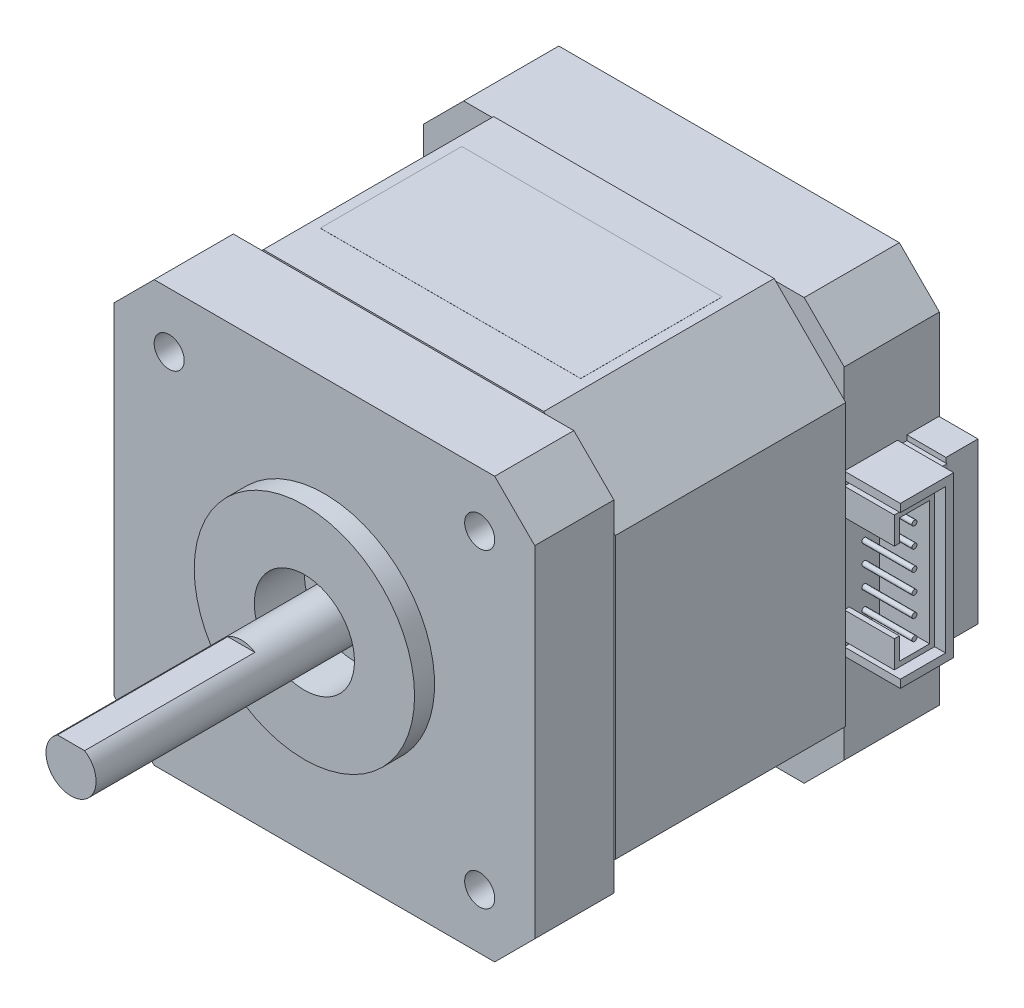
SolidWorks part; units mm, degrees
ref_plane "Front Plane" through (0, 0, 0) normal (0, 0, 1) x (1, 0, 0)
ref_plane "Top Plane" through (0, 0, 0) normal (0, 1, 0) x (1, 0, 0)
ref_plane "Right Plane" through (0, 0, 0) normal (1, 0, 0) x (0, 0, -1)
sketch "Sketch1" plane through (0, 0, 0) normal (0, 0, 1) x (1, 0, 0)
  line L0 (-17, 21) -> (-21, 17)
  line L1 (-17, -21) -> (17, -21)
  line L2 (-21, -17) -> (-21, 17)
  line L3 (-17, 21) -> (17, 21)
  line L4 (21, -17) -> (21, 17)
  line L5 (21, 17) -> (17, 21)
  line L6 (17, -21) -> (21, -17)
  line L12 (-21, -17) -> (-17, -21)
  point P0 (0, 0)
  point P15 (0, 0)
  dimension "D1" = 4
extrude "Boss-Extrude1" add sketch "Sketch1" along normal blind 9.5
sketch "Sketch2" plane through (0, 0, 9.5) normal (0, 0, 1) x (1, 0, 0)
  line L0 (14, 21.15) -> (21.15, 14)
  line L5 (-14, -21.15) -> (14, -21.15)
  line L6 (-21.15, -14) -> (-21.15, 14)
  line L7 (-14, 21.15) -> (14, 21.15)
  line L12 (21.15, -14) -> (21.15, 14)
  line L14 (17.5, -17.5) -> (17.575, -17.575) construction
  line L15 (-21.15, 14) -> (-14, 21.15)
  line L16 (21.15, -14) -> (14, -21.15)
  line L17 (-14, -21.15) -> (-21.15, -14)
  line L18 (17.5, 17.5) -> (17.575, 17.575) construction
  point P0 (0, 0)
  point P1 (0, 0)
  point P13 (0, 0)
  point P16 (0, 0)
  point P19 (0, 0)
  point P22 (0, 0)
  point P29 (0, 0)
  dimension "D1" = 4
  dimension "D5" = 4
extrude "Boss-Extrude2" add sketch "Sketch2" along normal blind 23
sketch "Sketch3" plane through (0, 0, 32.5) normal (0, 0, 1) x (1, 0, 0)
  line L0 (-17, 21) -> (17, 21)
  line L1 (17, 21) -> (21, 17)
  line L2 (21, 17) -> (21, -17)
  line L3 (21, -17) -> (17, -21)
  line L4 (17, -21) -> (-17, -21)
  line L5 (-17, -21) -> (-21, -17)
  line L6 (-21, -17) -> (-21, 17)
  line L7 (-21, 17) -> (-17, 21)
extrude "Boss-Extrude3" add sketch "Sketch3" along normal blind 7.9
sketch "Sketch5" plane through (0, 0, 40.4) normal (0, 0, 1) x (1, 0, 0)
  circle A0 centre (0, 0) radius 11
  circle A1 centre (0, 0) radius 5
  dimension "D1" = 22
  dimension "D2" = 10
extrude "Boss-Extrude4" add sketch "Sketch5" along normal blind 2
sketch "Sketch6" plane through (0, 0, 40.4) normal (0, 0, 1) x (1, 0, 0)
  circle A0 centre (0, 0) radius 5
extrude "Cut-Extrude1" cut sketch "Sketch6" against normal blind 3
sketch "Sketch7" plane through (0, 0, 37.4) normal (0, 0, 1) x (1, 0, 0)
  circle A0 centre (0, 0) radius 2.5
  dimension "D1" = 5
extrude "Boss-Extrude5" add sketch "Sketch7" along normal up to surface (5 mm away) up to face at (11, 0, 42.4)
sketch "Sketch8" plane through (0, 0, 42.4) normal (0, 0, 1) x (1, 0, 0)
  circle A0 centre (0, 0) radius 2.5
extrude "Boss-Extrude6" add sketch "Sketch8" along normal blind 23.3
sketch "Sketch9" plane through (0, 0, 65.7) normal (0, 0, 1) x (1, 0, 0)
  line L0 (-2.3166, 2.1) -> (3.6979, 2.1)
  line L1 (3.6979, 2.1) -> (-0.1236, 3.991)
  line L2 (-0.1236, 3.991) -> (-2.3166, 2.1)
extrude "Cut-Extrude2" cut sketch "Sketch9" against normal blind 17
sketch "Sketch10" plane through (0, 21.15, 0) normal (0, 1, 0) x (1, 0, 0)
  line L1 (-13, -13.6909) -> (13, -13.6909)
  line L3 (-13, -27.8113) -> (13, -27.8113)
  line L6 (-13, -13.6909) -> (-13, -27.8113)
  line L8 (13, -13.6909) -> (13, -27.8113)
extrude "Boss-Extrude7" add sketch "Sketch10" along normal blind 0.01
sketch "Sketch11" plane through (21, 0, 0) normal (1, 0, 0) x (0, 0, -1)
  line L1 (-3.2456, -8) -> (-0.0456, -8)
  line L3 (-3.2456, 8) -> (-0.0456, 8)
  line L5 (-3.2456, 8) -> (-3.2456, -8)
  line L7 (-0.0456, 8) -> (-0.0456, -8)
  point P0 (0, 0)
  dimension "D2" = 3.2
extrude "Boss-Extrude8" add sketch "Sketch11" along normal blind 3.9
sketch "Sketch12" plane through (21, 0, 0) normal (1, 0, 0) x (0, 0, -1)
  line L0 (-9.5, -14.15) -> (-9.5, 14.15) construction
  line L2 (-9.5, 7.479) -> (-9.5, 7.2)
  line L5 (-0.0456, 8) -> (-3.2456, 8) construction
  line L6 (-9.5, 7.2) -> (-4.9761, 7.2)
  line L9 (-4.1761, 7.2) -> (-4.1761, -7.2)
  line L10 (-4.1761, 8) -> (-9.5, 8)
  line L11 (-9.5, -14) -> (-9.5, 14) construction
  line L12 (-9.5, 7.479) -> (-9.5, 7.2)
  line L13 (-0.0456, 0) -> (6.3047, 0) construction
  line L14 (-0.0456, -8) -> (-0.0456, 8) construction
  line L15 (-9.5, -7.2) -> (-4.9761, -7.2)
  line L16 (-9.5, 7.2) -> (-9.5, 8)
  line L17 (-9.5, -7.2) -> (-9.5, -8)
  line L19 (-4.1761, -8) -> (-9.5, -8)
  line L20 (-4.9761, 7.2) -> (-4.9761, -7.2)
  line L21 (-4.1761, 8) -> (-4.1761, 7.2)
  line L22 (-4.1761, -7.2) -> (-4.1761, -8)
  dimension "D1" = 0.8
  dimension "D2" = 0.8
extrude "Boss-Extrude9" add sketch "Sketch12" along normal blind 5.6 contours L16 L10 L21 L9 L22 L19 L17 L15 L20 L6
sketch "Sketch13" plane through (21, 0, 0) normal (1, 0, 0) x (0, 0, -1)
  line L0 (-4.1761, 8) -> (-4.1761, -8) construction
  line L1 (-4.1761, 7.5) -> (-3.2456, 7.5)
  line L2 (-4.1761, 7.5) -> (-4.1761, -7.5)
  line L3 (-4.1761, -7.5) -> (-3.2456, -7.5)
  line L4 (-3.2456, 7.5) -> (-3.2456, -7.5)
  line L5 (-3.2456, 8) -> (-3.2456, -8) construction
  line L6 (-0.0456, 8) -> (-3.2456, 8) construction
  line L7 (-3.2456, -8) -> (-0.0456, -8) construction
  dimension "D1" = 0.5
  dimension "D2" = 0.5
extrude "Boss-Extrude10" add sketch "Sketch13" along normal up to surface (3.9 mm away) up to face at (24.9, 0, 1.6456)
sketch "Sketch14" plane through (24.9, 0, 0) normal (1, 0, 0) x (0, 0, -1)
  line L1 (-4.1761, 7.5) -> (-3.2456, 7.5)
  line L2 (-4.1761, 7.5) -> (-4.1761, -7.5)
  line L3 (-4.1761, -7.5) -> (-3.2456, -7.5)
  line L4 (-3.2456, 7.5) -> (-3.2456, -7.5)
extrude "Boss-Extrude11" add sketch "Sketch14" along normal blind 0.1
sketch "Sketch15" plane through (21, 0, 0) normal (1, 0, 0) x (0, 0, -1)
  line L0 (-5.9761, 6.2) -> (-9, 6.2)
  line L5 (0, 0) -> (5.9447, 0) construction
  line L6 (-9.5, -7.2) -> (-9.5, 7.2) construction
  line L7 (-9.5, 4) -> (-9, 4)
  line L9 (-9.5, -4) -> (-9, -4)
  line L11 (-9.5, 7.2) -> (-4.9761, 7.2) construction
  line L12 (-9, 6.7) -> (-5.4761, 6.7)
  line L13 (-9, 6.2) -> (-9, 4)
  line L14 (-9, -6.7) -> (-5.4761, -6.7)
  line L15 (-5.4761, 6.7) -> (-5.4761, -6.7)
  line L16 (-4.9761, 7.2) -> (-4.9761, -7.2) construction
  line L17 (-9, 6.7) -> (-9.5, 6.7)
  line L18 (-9.5, -7.2) -> (-9.5, 7.2) construction
  line L19 (-9.5, 6.7) -> (-9.5, 4)
  line L20 (-5.9761, 6.2) -> (-5.9761, -6.2)
  line L21 (-9.5, -7.2) -> (-4.9761, -7.2) construction
  line L22 (-9, -6.2) -> (-5.9761, -6.2)
  line L23 (-9.5, -4) -> (-9.5, -6.7)
  line L24 (-9.5, -6.7) -> (-9, -6.7)
  line L25 (-9, -4) -> (-9, -6.2)
  dimension "D1" = 4
  dimension "D2" = 4
  dimension "D4" = 0.5
  dimension "D5" = 0.5
  dimension "D6" = 0.5
  dimension "D7" = 0.5
  dimension "D8" = 0.5
  dimension "D9" = 0.5
extrude "Boss-Extrude12" add sketch "Sketch15" along normal blind 5
sketch "Sketch16" plane through (21, 0, 0) normal (1, 0, 0) x (0, 0, -1)
  line L0 (-7.4881, 6.2) -> (-7.4881, 5) construction
  line L1 (-9, 6.2) -> (-5.9761, 6.2) construction
  circle A0 centre (-7.4881, 5) radius 0.25
  circle A1 centre (-7.4881, 3) radius 0.25
  circle A2 centre (-7.4881, 1) radius 0.25
  circle A3 centre (-7.4881, -1) radius 0.25
  circle A4 centre (-7.4881, -3) radius 0.25
  circle A5 centre (-7.4881, -5) radius 0.25
  dimension "D2" = 0.5
  dimension "D1" = 1.2
  dimension "D3" = 6
extrude "Boss-Extrude13" add sketch "Sketch16" along normal blind 5
sketch "Sketch17" plane through (0, 0, 40.4) normal (0, 0, 1) x (1, 0, 0)
  circle A0 centre (-15.5, 15.5) radius 1.5
  circle A1 centre (15.5, 15.5) radius 1.5
  circle A2 centre (15.5, -15.5) radius 1.5
  circle A3 centre (-15.5, -15.5) radius 1.5
  point P0 (0, 0)
  point P13 (0, 0)
  dimension "D3" = 3
  dimension "D1" = 4
extrude "Cut-Extrude3" cut sketch "Sketch17" against normal blind 5.5
sketch "Sketch18" plane through (0, 0, 0) normal (0, 0, -1) x (-1, 0, 0)
  circle A0 centre (-15.5, 15.5) radius 3.25
  circle A1 centre (15.5, 15.5) radius 3.25
  circle A2 centre (15.5, -15.5) radius 3.25
  circle A3 centre (-15.5, -15.5) radius 3.25
  point P0 (0, 0)
  point P13 (0, 0)
  dimension "D3" = 6.5
  dimension "D1" = 4
extrude "Cut-Extrude4" cut sketch "Sketch18" against normal blind 3
sketch "Sketch20" plane through (0, 0, 3) normal (0, 0, -1) x (-1, 0, 0)
  circle A0 centre (-15.5, 15.5) radius 1.5
  circle A1 centre (15.5, 15.5) radius 1.5
  circle A2 centre (-15.5, -15.5) radius 1.5
  circle A3 centre (15.5, -15.5) radius 1.5
  dimension "D1" = 3
  dimension "D2" = 3
  dimension "D3" = 3
  dimension "D4" = 3
extrude "Cut-Extrude5" cut sketch "Sketch20" against normal blind 4
sketch "Sketch21" plane through (0, 0, 0) normal (0, 0, -1) x (-1, 0, 0)
  circle A0 centre (0, 0) radius 4.5
  dimension "D1" = 9
extrude "Cut-Extrude6" cut sketch "Sketch21" against normal blind 4
